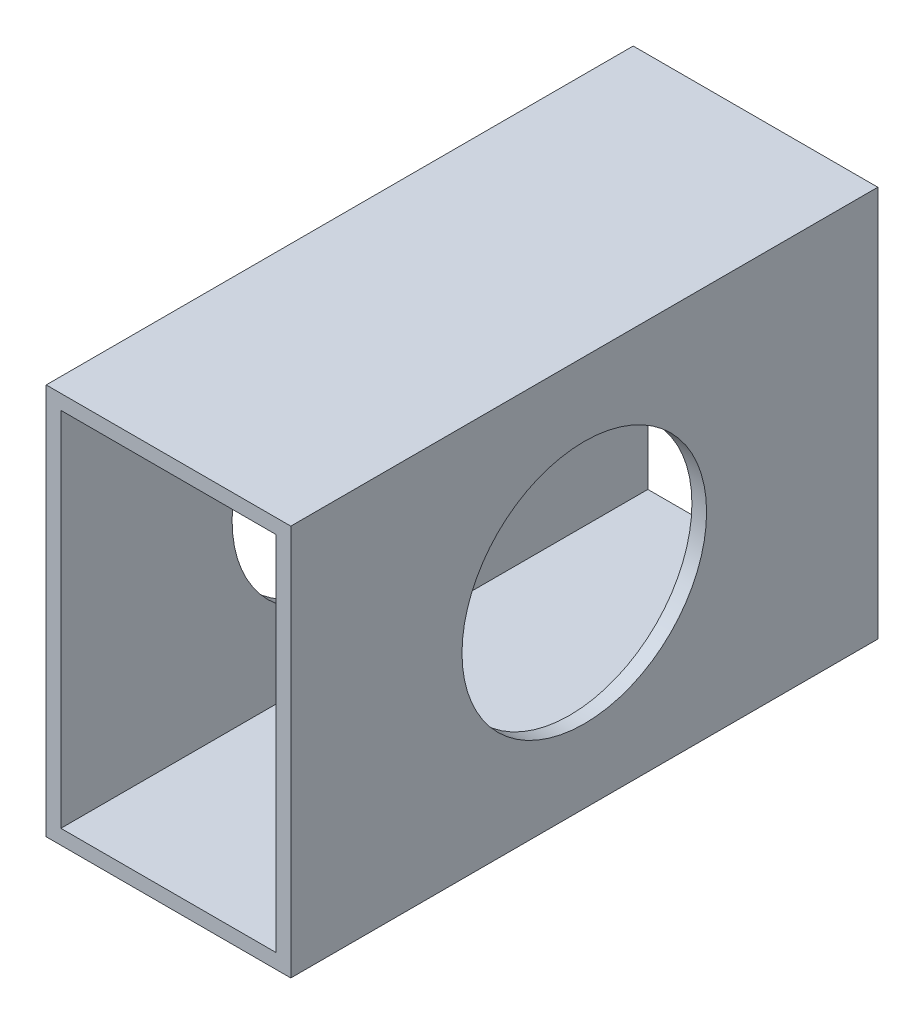
SolidWorks part; units mm, degrees
ref_plane "Płaszczyzna przednia" through (0, 0, 0) normal (0, 0, 1) x (1, 0, 0)
ref_plane "Płaszczyzna górna" through (0, 0, 0) normal (0, 1, 0) x (1, 0, 0)
ref_plane "Płaszczyzna prawa" through (0, 0, 0) normal (1, 0, 0) x (0, 0, -1)
sketch "Szkic1" plane through (0, 0, 0) normal (0, 0, 1) x (1, 0, 0)
  line L1 (-25, -40) -> (25, -40)
  line L2 (-25, -40) -> (-25, 40)
  line L3 (-25, 40) -> (25, 40)
  line L4 (25, -40) -> (25, 40)
  line L5 (-25, -40) -> (25, 40) construction
  line L6 (-25, 40) -> (25, -40) construction
  line L7 (-22, -37) -> (22, -37)
  line L8 (-22, -37) -> (-22, 37)
  line L9 (-22, 37) -> (22, 37)
  line L10 (22, -37) -> (22, 37)
  line L11 (-22, -37) -> (22, 37) construction
  line L12 (-22, 37) -> (22, -37) construction
  point P0 (0, 0)
  point P5 (0, 0)
  dimension "D1" = 80
  dimension "D2" = 50
  dimension "D3" = 3
  dimension "D4" = 3
extrude "Dodanie-wyciągnięcie1" add sketch "Szkic1" along normal blind 120
sketch "Szkic2" plane through (25, 0, 0) normal (1, 0, 0) x (0, 0, -1)
  line L2 (-60, 46.7052) -> (-60, 27.4639) construction
  line L3 (0, -40) -> (0, 40) construction
  line L4 (-120, -40) -> (-120, 40) construction
  circle A0 centre (-60, 0) radius 25
  dimension "D1" = 50
extrude "Wytnij-wyciągnięcie1" cut sketch "Szkic2" against normal through all contours A0
